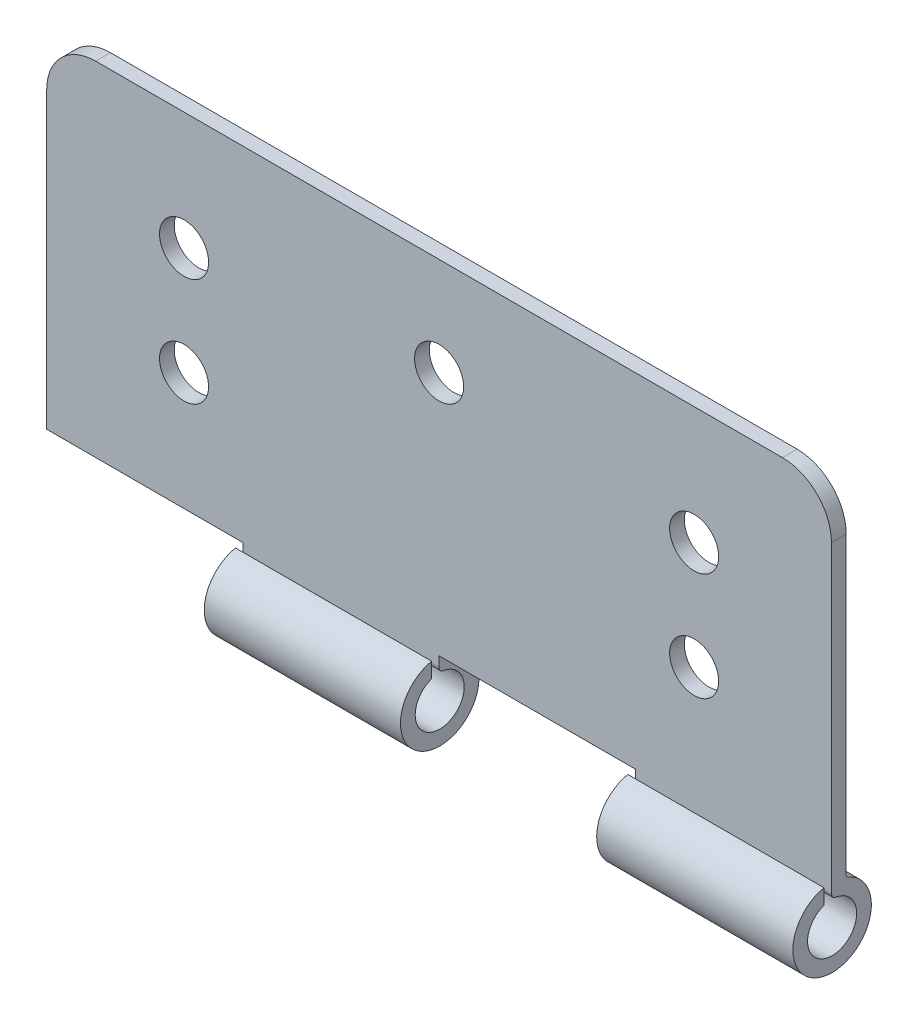
SolidWorks part; units mm, degrees
ref_plane "Front Plane" through (0, 0, 0) normal (0, 0, 1) x (1, 0, 0)
ref_plane "Top Plane" through (0, 0, 0) normal (0, 1, 0) x (1, 0, 0)
ref_plane "Right Plane" through (0, 0, 0) normal (1, 0, 0) x (0, 0, -1)
sketch "Sketch2" plane through (0, 0, 0) normal (0, 0, 1) x (1, 0, 0)
  line L1 (40, -17.5) -> (-40, -17.5)
  line L2 (40, -17.5) -> (40, 12.5)
  line L3 (35, 17.5) -> (-35, 17.5)
  line L4 (-40, -17.5) -> (-40, 12.5)
  line L5 (40, -17.5) -> (-40, 17.5) construction
  line L6 (40, 17.5) -> (-40, -17.5) construction
  arc A0 (40, 12.5) -> (35, 17.5) centre (35, 12.5) ccw
  arc A1 (-35, 17.5) -> (-40, 12.5) centre (-35, 12.5) ccw
  point P0 (0, 0)
  dimension "D3" = 5
  dimension "D1" = 80
  dimension "D2" = 35
extrude "Boss-Extrude1" add sketch "Sketch2" along normal blind 1.5
sketch "Sketch6" plane through (40, 0, 0) normal (1, 0, 0) x (0, 0, -1)
  line L0 (-2.2648, -17.586) -> (-2.2648, -19.1403)
  line L1 (0, -17.5) -> (0, -17.5989)
  line L2 (0, -17.5) -> (-1.5, -17.5)
  line L3 (-1.5, -17.5) -> (-1.5, -18.5316)
  arc A0 (-2.2648, -17.586) -> (0.1507, -17.8284) centre (-1.4376, -21.4995) ccw
  arc A1 (-2.2648, -19.1403) -> (-1.0729, -19.0263) centre (-1.4376, -21.4995) ccw
  arc A2 (-1.5, -18.5316) -> (-1.0729, -19.0263) centre (-1, -18.5316) ccw
  arc A3 (0, -17.5989) -> (0.1507, -17.8284) centre (0.25, -17.5989) ccw
  dimension "D1" = 0.5
  dimension "D2" = 0.25
extrude "Boss-Extrude3" add sketch "Sketch6" against normal blind 20
pattern_linear "LPattern1" count 2 spacing 40 along (-1, 0, 0) of "Boss-Extrude3"
sketch "Sketch7" plane through (0, 0, 1.5) normal (0, 0, 1) x (1, 0, 0)
  line L0 (40, -18.5316) -> (40, 12.5) construction
  line L1 (0, -17.5) -> (20, -17.5) construction
  line L2 (-40, -17.5) -> (-20, -17.5) construction
  line L3 (-40, 12.5) -> (-40, -17.5) construction
  line L4 (35, 17.5) -> (-35, 17.5) construction
  circle A0 centre (0, 7.5) radius 2.5
  circle A1 centre (-26, -5.5) radius 2.5
  circle A2 centre (26, -5.5) radius 2.5
  point P16 (0, 17.5)
  dimension "D1" = 5
  dimension "D2" = 5
  dimension "D3" = 5
  dimension "D4" = 14
  dimension "D5" = 12
  dimension "D6" = 12
  dimension "D7" = 14
  dimension "D8" = 10
extrude "Cut-Extrude1" cut sketch "Sketch7" against normal through all
sketch "Sketch8" plane through (0, 0, 1.5) normal (0, 0, 1) x (1, 0, 0)
  line L0 (-40, 12.5) -> (-40, -17.5) construction
  line L1 (35, 17.5) -> (-35, 17.5) construction
  line L2 (40, -18.5316) -> (40, 12.5) construction
  circle A0 centre (-26, 5.5) radius 2.5
  circle A1 centre (26, 5.5) radius 2.5
  dimension "D1" = 14
  dimension "D2" = 12
  dimension "D3" = 14
  dimension "D4" = 12
extrude "Cut-Extrude2" cut sketch "Sketch8" against normal through all
